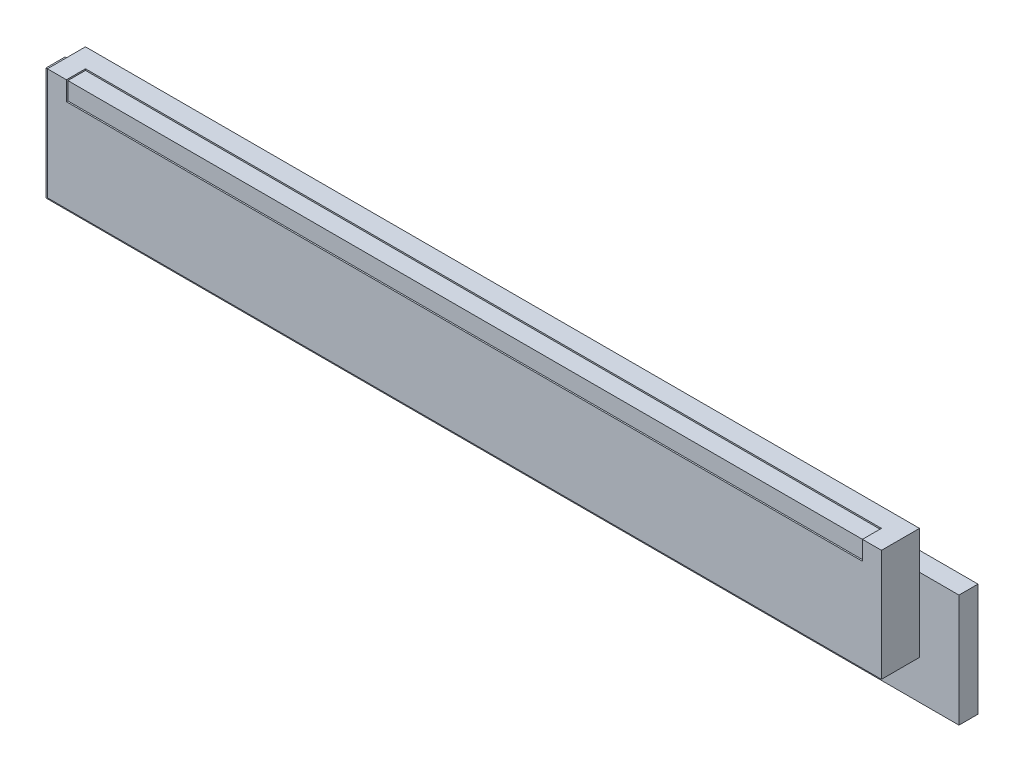
SolidWorks part; units mm, degrees
ref_plane "Front Plane" through (0, 0, 0) normal (0, 0, 1) x (1, 0, 0)
ref_plane "Top Plane" through (0, 0, 0) normal (0, 1, 0) x (1, 0, 0)
ref_plane "Right Plane" through (0, 0, 0) normal (1, 0, 0) x (0, 0, -1)
sketch "Sketch1" plane through (0, 0, 0) normal (0, 0, 1) x (1, 0, 0)
  line L1 (-960, 118.5) -> (960, 118.5)
  line L2 (-960, 118.5) -> (-960, -118.5)
  line L3 (-960, -118.5) -> (960, -118.5)
  line L4 (960, 118.5) -> (960, -118.5)
  line L5 (-960, 118.5) -> (960, -118.5) construction
  line L6 (-960, -118.5) -> (960, 118.5) construction
  point P0 (0, 0)
  dimension "D1" = 237
  dimension "D2" = 1920
extrude "Boss-Extrude1" add sketch "Sketch1" along normal blind 40
ref_plane "Plane1" through (0, 0, 40) normal (0, 0, 1) x (1, 0, 0)
sketch "Sketch2" plane through (0, 0, 40) normal (0, 0, 1) x (1, 0, 0)
  line L0 (-960, -118.5) -> (960, -118.5) construction
  line L1 (-960, -118.5) -> (960, -118.5)
  line L2 (960, -118.5) -> (960, 198.5)
  line L3 (-960, -118.5) -> (-960, 198.5)
  line L4 (-960, 198.5) -> (960, 198.5)
  dimension "D1" = 317
  dimension "D2" = 317
extrude "Boss-Extrude2" add sketch "Sketch2" along normal blind 80
ref_plane "Plane2" through (0, 198.5, 0) normal (0, 1, 0) x (1, 0, 0)
sketch "Sketch3" plane through (0, 198.5, 0) normal (0, 1, 0) x (1, 0, 0)
  line L0 (-960, -120) -> (-960, 0) construction
  line L1 (960, -120) -> (960, 0) construction
  line L2 (-960, -120) -> (-960, -40)
  line L3 (960, -120) -> (960, -40)
  line L4 (-937, -120) -> (-937, -40)
  line L6 (-937, -120) -> (-960, -120)
  line L7 (937, -120) -> (937, -40)
  line L9 (960, -120) -> (937, -120)
  line L10 (960, -40) -> (-960, -40) construction
  line L11 (960, -40) -> (937, -40)
  line L12 (960, -120) -> (960, 0) construction
  line L13 (937, -120) -> (937, 0) construction
  line L14 (-937, -40) -> (-960, -40)
  line L15 (-960, -120) -> (-960, 0) construction
  line L16 (-937, -120) -> (-937, 0) construction
  dimension "D1" = 23
  dimension "D2" = 23
extrude "Cut-Extrude2" cut sketch "Sketch3" against normal through all
ref_plane "Plane3" through (937, 0, 0) normal (1, 0, 0) x (0, 0, -1)
sketch "Sketch6" plane through (937, 0, 0) normal (1, 0, 0) x (0, 0, -1)
  line L0 (-40, -118.5) -> (-120, -118.5) construction
  line L1 (-40, -118.5) -> (-120, -118.5)
  line L2 (-40, -36.5) -> (-120, -36.5)
  line L3 (-120, -36.5) -> (-120, -118.5)
  line L4 (-40, -36.5) -> (-40, -118.5)
  dimension "D1" = 82
extrude "Cut-Extrude3" cut sketch "Sketch6" against normal through all
ref_plane "Plane4" through (0, 198.5, 0) normal (0, 1, 0) x (1, 0, 0)
sketch "Sketch7" plane through (0, 198.5, 0) normal (0, 1, 0) x (1, 0, 0)
  line L0 (877, -120) -> (877, -40)
  line L1 (-877, -40) -> (-877, -120)
  line L2 (937, -40) -> (877, -40)
  line L3 (877, -120) -> (937, -120)
  line L4 (937, -40) -> (-937, -40)
  line L5 (-937, -40) -> (-937, -120)
  line L6 (-937, -120) -> (937, -120)
  line L7 (937, -120) -> (937, -40)
  line L8 (937, -40) -> (877, -40)
  line L9 (-937, -40) -> (-937, -120)
  line L10 (-937, -120) -> (-877, -120)
  line L11 (937, -120) -> (937, -40)
  line L12 (877, -120) -> (937, -120)
  line L13 (-877, -40) -> (-937, -40)
  dimension "D1" = 0
  dimension "D2" = 60
extrude "Cut-Extrude4" cut sketch "Sketch7" against normal through all contours L1 L13 L9 L10 | L3 L11 L2 L0
ref_plane "Plane5" through (837, 0, 0) normal (1, 0, 0) x (0, 0, -1)
sketch "Sketch8" plane through (837, 0, 0) normal (1, 0, 0) x (0, 0, -1)
  line L3 (-120, 198.5) -> (-40, 198.5) construction
  line L4 (-120, -36.5) -> (-120, 198.5) construction
  line L5 (-117, -36.5) -> (-117, 195.5)
  line L6 (-117, 195.5) -> (-40, 195.5)
  line L7 (-117, 158.5) -> (-117, 195.5)
  line L8 (-117, 195.5) -> (-80, 195.5)
  line L9 (-120, 198.5) -> (-80, 198.5)
  line L10 (-120, 158.5) -> (-120, 198.5)
  line L11 (-80, 195.5) -> (-80, 198.5)
  line L12 (-120, 158.5) -> (-117, 158.5)
  line L13 (-120, -36.5) -> (-120, 198.5) construction
  line L14 (-80, -36.5) -> (-80, 198.5) construction
  line L15 (-120, 158.5) -> (-40, 158.5) construction
  line L16 (-120, 198.5) -> (-40, 198.5) construction
  dimension "D1" = 3
  dimension "D2" = 40
  dimension "D3" = 40
extrude "Cut-Extrude5" cut sketch "Sketch8" against normal offset from surface (1674 mm away) 40 up to face at (-877, 88.5, 72)
